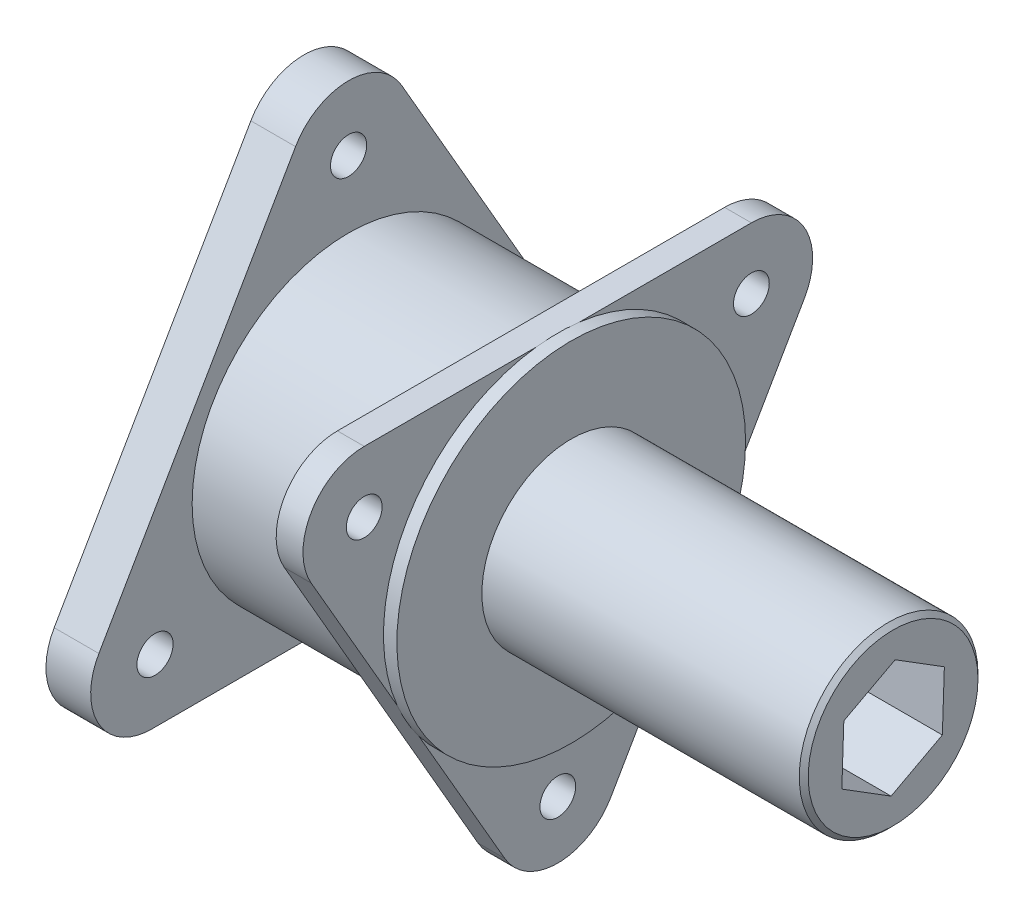
SolidWorks part; units mm, degrees
other "Markup1"
sketch "Sketch15" plane through (0, -64.5, 57.6941) normal (-0.9121, -0.2697, 0.3087) x (0.4098, -0.6172, 0.6716)
material "7075-T6 (SN)"
ref_plane "Front Plane" through (0, 0, 0) normal (0, 0, 1) x (1, 0, 0)
ref_plane "Top Plane" through (0, 0, 0) normal (0, 1, 0) x (1, 0, 0)
ref_plane "Right Plane" through (0, 0, 0) normal (1, 0, 0) x (0, 0, -1)
sketch "Sketch10" plane through (0, 0, 0) normal (1, 0, 0) x (0, 0, -1)
  line L0 (-55.8586, -18.55) -> (-11.8645, 57.65)
  line L1 (11.8645, 57.65) -> (55.8586, -18.55)
  line L2 (-43.9941, -39.1) -> (43.9941, -39.1)
  circle A0 centre (0, 0) radius 64.5 construction
  arc A5 (11.8645, 57.65) -> (-11.8645, 57.65) centre (0, 50.8) ccw
  arc A6 (43.9941, -39.1) -> (55.8586, -18.55) centre (43.9941, -25.4) ccw
  arc A7 (-55.8586, -18.55) -> (-43.9941, -39.1) centre (-43.9941, -25.4) ccw
  circle A8 centre (0, 0) radius 50 construction
  circle A9 centre (0, 50) radius 4.05
  circle A10 centre (43.3013, -25) radius 4.05
  circle A11 centre (-43.3013, -25) radius 4.05
  point P7 (0, 0)
  point P8 (-13.5749, 48.9527)
  point P9 (0, 0)
  point P10 (0, 0)
  point P12 (0, 0)
  point P13 (0, 0)
  point P18 (0, 0)
  point P19 (13.5749, 48.9527)
  point P20 (0, 0)
  point P28 (0, 0)
  dimension "D1" = 129
  dimension "D2" = 100
  dimension "D3" = 8.1
  dimension "D7" = 27.4
  dimension "D8" = 3
  dimension "D4" = 3
extrude "Boss-Extrude12" add sketch "Sketch10" along normal blind 10
sketch "Sketch11" plane through (10, 0, 0) normal (1, 0, 0) x (0, 0, -1)
  circle A0 centre (0, 0) radius 35
  dimension "D1" = 70
extrude "Boss-Extrude13" add sketch "Sketch11" along normal blind 40.8
sketch "Sketch12" plane through (50.8, 0, 0) normal (1, 0, 0) x (0, 0, -1)
  line L0 (-43.3013, 38.7) -> (43.3013, 38.7)
  line L1 (-55.1658, 18.15) -> (-11.8645, -56.85)
  line L2 (55.1658, 18.15) -> (11.8645, -56.85)
  circle A0 centre (0, 0) radius 50 construction
  circle A3 centre (43.3013, 25) radius 4
  circle A5 centre (0, -50.8) radius 4
  circle A7 centre (-43.3013, 25) radius 4
  arc A10 (-43.3013, 38.7) -> (-55.1658, 18.15) centre (-43.3013, 25) ccw
  arc A11 (55.1658, 18.15) -> (43.3013, 38.7) centre (43.3013, 25) ccw
  arc A12 (-11.8645, -56.85) -> (11.8645, -56.85) centre (0, -50) ccw
  point P4 (0, 0)
  point P7 (0, 0)
  point P11 (0, 0)
  point P15 (0, 0)
  point P19 (0, 0)
  point P20 (0, 0)
  point P21 (0, 0)
  dimension "D1" = 100
  dimension "D2" = 27.4
  dimension "D3" = 3
extrude "Boss-Extrude14" add sketch "Sketch12" along normal blind 6
sketch "Sketch13" plane through (56.8, 0, 0) normal (1, 0, 0) x (0, 0, -1)
  circle A0 centre (0, 0) radius 19.993
  dimension "D1" = 39.986
extrude "Boss-Extrude15" add sketch "Sketch13" along normal blind 75
sketch "Sketch14" plane through (131.8, 0, 0) normal (1, 0, 0) x (0, 0, -1)
  line L1 (-11.4662, -6.1054) -> (-0.4456, -12.9827)
  line L2 (-0.4456, -12.9827) -> (11.0206, -6.8773)
  line L3 (11.0206, -6.8773) -> (11.4662, 6.1054)
  line L4 (11.4662, 6.1054) -> (0.4456, 12.9827)
  line L5 (0.4456, 12.9827) -> (-11.0206, 6.8773)
  line L6 (-11.0206, 6.8773) -> (-11.4662, -6.1054)
  circle A0 centre (0, 0) radius 11.25 construction
  dimension "D1" = 22.5
sketch "Sketch16" plane through (56.8, 0, 0) normal (1, 0, 0) x (0, 0, -1)
  circle A0 centre (0, 0) radius 39
  dimension "D1" = 78
extrude "Boss-Extrude16" add sketch "Sketch16" along normal blind 3
chamfer "Chamfer1" distance 1 angle 45 1 edges at (131.8, 0, -19.993)
extrude "Cut-Extrude2" cut sketch "Sketch14" against normal up to surface (131.8 mm away) up to face at (0, 0, 0)
